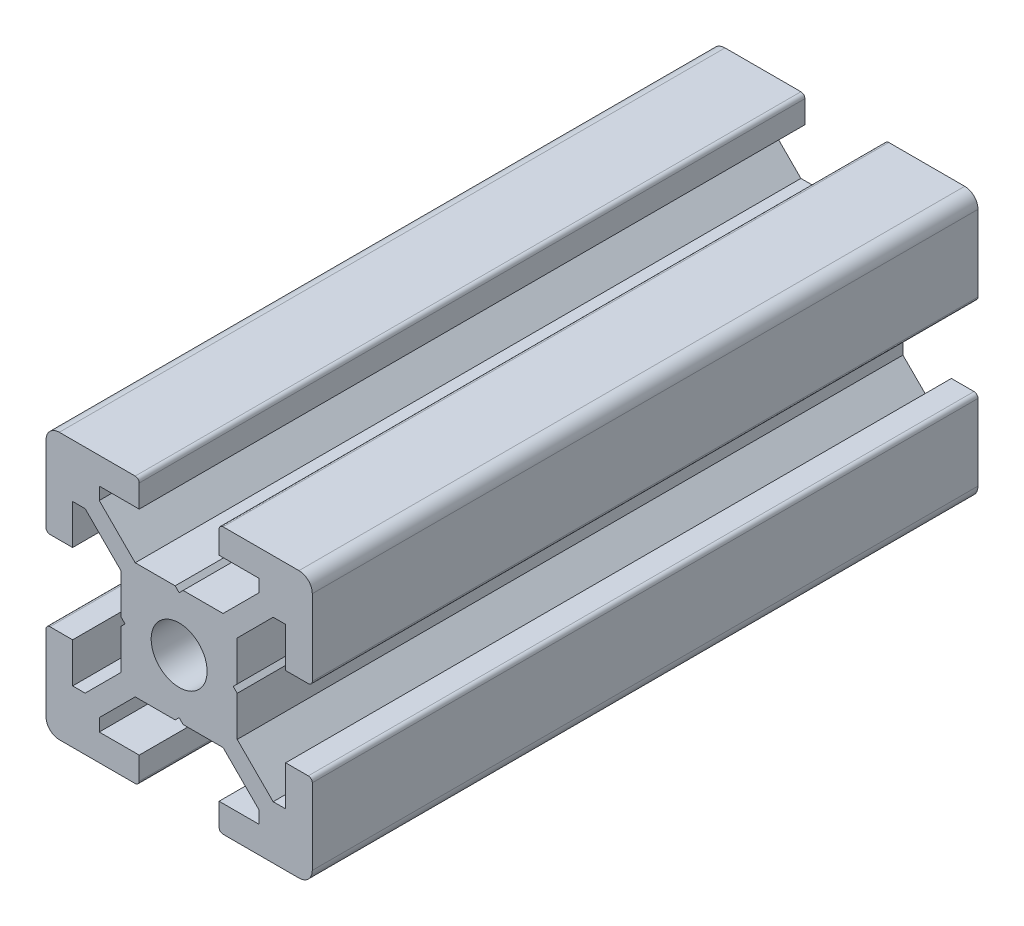
SolidWorks part; units mm, degrees
ref_plane "Front Plane" through (0, 0, 0) normal (0, 0, 1) x (1, 0, 0)
ref_plane "Top Plane" through (0, 0, 0) normal (0, 1, 0) x (1, 0, 0)
ref_plane "Right Plane" through (0, 0, 0) normal (1, 0, 0) x (0, 0, -1)
sketch "Sketch1" plane through (0, 0, 0) normal (0, 0, 1) x (1, 0, 0)
  line L0 (0, 0) -> (0, 4.3607) construction
  line L1 (-10, 10) -> (10, 10) construction
  line L2 (-10, 10) -> (-10, -10) construction
  line L3 (-10, -10) -> (10, -10) construction
  line L4 (10, 10) -> (10, -10) construction
  line L5 (-10, 10) -> (10, -10) construction
  line L6 (-10, -10) -> (10, 10) construction
  line L7 (0, 4.3607) -> (3.3, 4.3607) construction
  line L8 (3.3, 4.3607) -> (6, 7.0607)
  line L9 (6, 7.0607) -> (6, 8)
  line L10 (6, 8) -> (3, 8)
  line L11 (3, 8) -> (3, 9.7)
  line L12 (3.3, 10) -> (9, 10)
  line L13 (0, 4.0607) -> (0.3, 4.3607)
  line L14 (0.3, 4.3607) -> (3.3, 4.3607)
  line L15 (10, 3.3) -> (10, 9)
  line L16 (8, 3) -> (9.7, 3)
  line L17 (8, 6) -> (8, 3)
  line L18 (7.0607, 6) -> (8, 6)
  line L19 (4.3607, 3.3) -> (7.0607, 6)
  line L20 (4.3607, 0.3) -> (4.3607, 3.3)
  line L21 (4.0607, 0) -> (4.3607, 0.3)
  line L22 (4.0607, 0) -> (4.3607, -0.3)
  line L23 (4.3607, -0.3) -> (4.3607, -3.3)
  line L24 (4.3607, -3.3) -> (7.0607, -6)
  line L25 (7.0607, -6) -> (8, -6)
  line L26 (8, -6) -> (8, -3)
  line L27 (8, -3) -> (9.7, -3)
  line L28 (10, -3.3) -> (10, -9)
  line L29 (3.3, -10) -> (9, -10)
  line L30 (3, -8) -> (3, -9.7)
  line L31 (6, -8) -> (3, -8)
  line L32 (6, -7.0607) -> (6, -8)
  line L33 (3.3, -4.3607) -> (6, -7.0607)
  line L34 (0.3, -4.3607) -> (3.3, -4.3607)
  line L35 (0, -4.0607) -> (0.3, -4.3607)
  line L36 (0, -4.0607) -> (-0.3, -4.3607)
  line L37 (-0.3, -4.3607) -> (-3.3, -4.3607)
  line L38 (-3.3, -4.3607) -> (-6, -7.0607)
  line L39 (-6, -7.0607) -> (-6, -8)
  line L40 (-6, -8) -> (-3, -8)
  line L41 (-3, -8) -> (-3, -9.7)
  line L42 (-3.3, -10) -> (-9, -10)
  line L43 (-10, -3.3) -> (-10, -9)
  line L44 (-8, -3) -> (-9.7, -3)
  line L45 (-8, -6) -> (-8, -3)
  line L46 (-7.0607, -6) -> (-8, -6)
  line L47 (-4.3607, -3.3) -> (-7.0607, -6)
  line L48 (-4.3607, -0.3) -> (-4.3607, -3.3)
  line L49 (-4.0607, 0) -> (-4.3607, -0.3)
  line L50 (-4.0607, 0) -> (-4.3607, 0.3)
  line L51 (-4.3607, 0.3) -> (-4.3607, 3.3)
  line L52 (-4.3607, 3.3) -> (-7.0607, 6)
  line L53 (-7.0607, 6) -> (-8, 6)
  line L54 (-8, 6) -> (-8, 3)
  line L55 (-8, 3) -> (-9.7, 3)
  line L56 (-10, 3.3) -> (-10, 9)
  line L57 (-3.3, 10) -> (-9, 10)
  line L58 (-3, 8) -> (-3, 9.7)
  line L59 (-6, 8) -> (-3, 8)
  line L60 (-6, 7.0607) -> (-6, 8)
  line L61 (-3.3, 4.3607) -> (-6, 7.0607)
  line L62 (-0.3, 4.3607) -> (-3.3, 4.3607)
  line L63 (0, 4.0607) -> (-0.3, 4.3607)
  arc A0 (3, 9.7) -> (3.3, 10) centre (3.3, 9.7) cw
  arc A1 (9, 10) -> (10, 9) centre (9, 9) cw
  arc A2 (9.7, 3) -> (10, 3.3) centre (9.7, 3.3) ccw
  arc A3 (9.7, -3) -> (10, -3.3) centre (9.7, -3.3) cw
  arc A4 (10, -9) -> (9, -10) centre (9, -9) cw
  arc A5 (3, -9.7) -> (3.3, -10) centre (3.3, -9.7) ccw
  arc A6 (-3, -9.7) -> (-3.3, -10) centre (-3.3, -9.7) cw
  arc A7 (-9, -10) -> (-10, -9) centre (-9, -9) cw
  arc A8 (-9.7, -3) -> (-10, -3.3) centre (-9.7, -3.3) ccw
  arc A9 (-9.7, 3) -> (-10, 3.3) centre (-9.7, 3.3) cw
  arc A10 (-10, 9) -> (-9, 10) centre (-9, 9) cw
  arc A11 (-3, 9.7) -> (-3.3, 10) centre (-3.3, 9.7) ccw
  circle A12 centre (0, 0) radius 2.1
  point P0 (0, 0)
  point P95 (0, 0)
  dimension "D4" = 1
  dimension "D5" = 0.3
  dimension "D12" = 4.2
  dimension "D1" = 20
  dimension "D2" = 20
  dimension "D3" = 2
  dimension "D6" = 0.75
  dimension "D7" = 3
  dimension "D8" = 0.9393
  dimension "D9" = 3
  dimension "D10" = 0.3
  dimension "D11" = 4
extrude "Boss-Extrude1" add sketch "Sketch1" along normal blind 50
